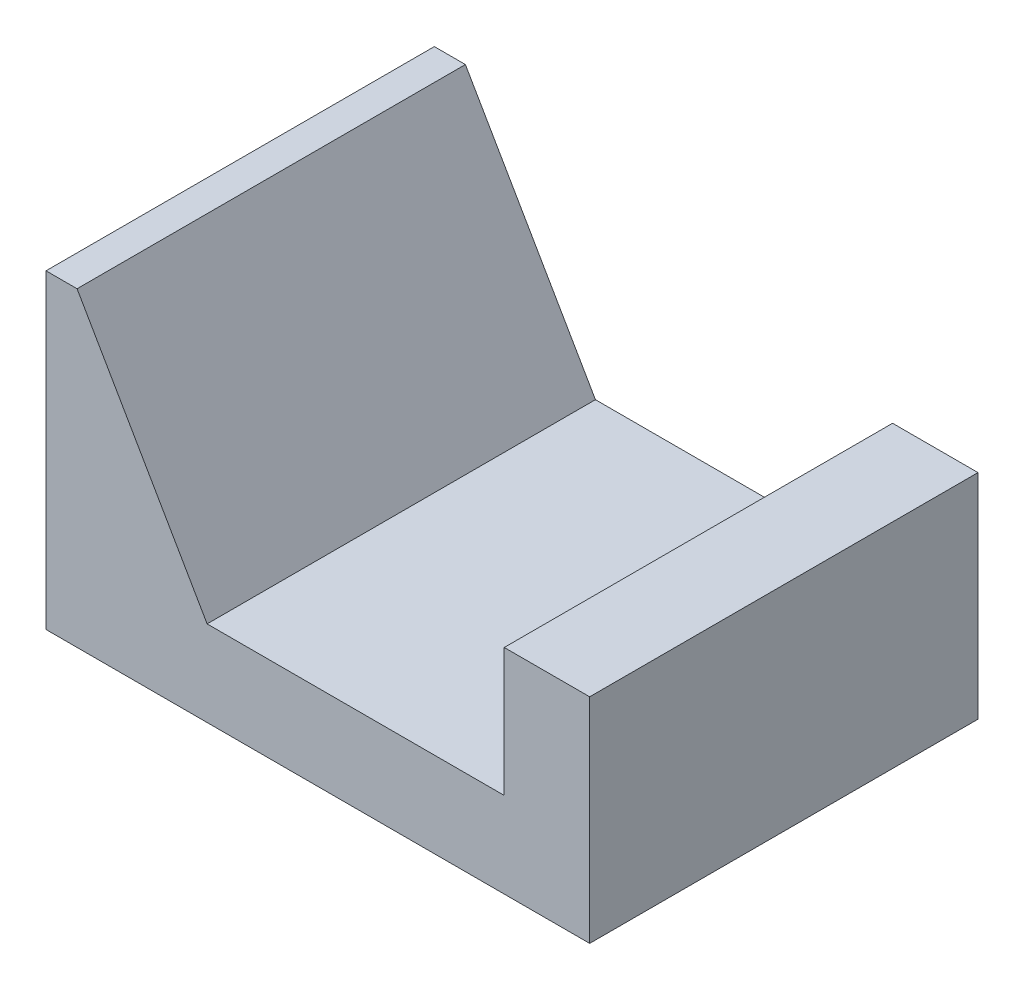
SolidWorks part; units mm, degrees
ref_plane "정면" through (0, 0, 0) normal (0, 0, 1) x (1, 0, 0)
ref_plane "윗면" through (0, 0, 0) normal (0, 1, 0) x (1, 0, 0)
ref_plane "우측면" through (0, 0, 0) normal (1, 0, 0) x (0, 0, -1)
sketch "스케치4" plane through (0, 0, 0) normal (0, 1, 0) x (1, 0, 0)
  line L1 (0, 0) -> (56, 0)
  line L2 (0, 0) -> (0, 40)
  line L3 (0, 40) -> (56, 40)
  line L4 (56, 0) -> (56, 40)
  dimension "D1" = 40
  dimension "D2" = 56
extrude "보스-돌출2" add sketch "스케치4" along normal blind 8.8
sketch "스케치5" plane through (0, 0, 0) normal (0, 0, 1) x (1, 0, 0)
  line L0 (0, 8.8) -> (0, 32)
  line L1 (0, 32) -> (3.2, 32)
  line L2 (3.2, 32) -> (16.5945, 8.8)
  line L3 (0, 8.8) -> (56, 8.8) construction
  line L4 (16.5945, 8.8) -> (0, 8.8)
  line L5 (0, 0) -> (56, 0) construction
  line L6 (56, 8.8) -> (47.2, 8.8)
  line L7 (56, 8.8) -> (56, 22)
  line L8 (56, 22) -> (47.2, 22)
  line L9 (47.2, 8.8) -> (47.2, 22)
  dimension "D1" = 8.8
  dimension "D2" = 22
  dimension "D3" = 3.2
  dimension "D4" = 32
  dimension "D5" = 30
extrude "보스-돌출3" add sketch "스케치5" against normal up to surface (40 mm away) up to face at (28, 4.4, -40)
